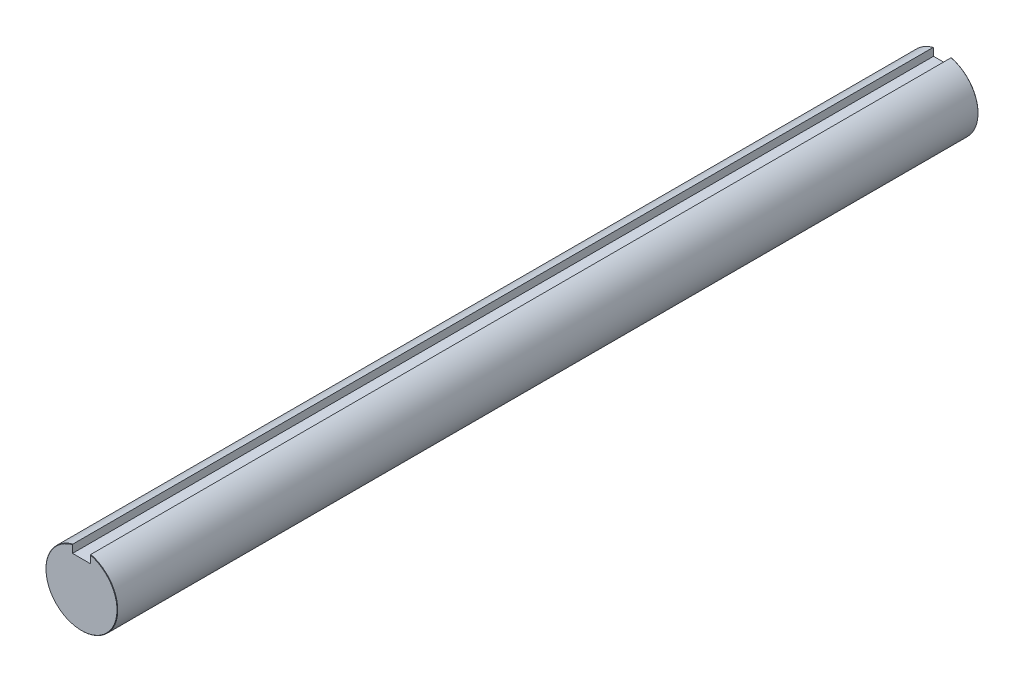
SolidWorks part; units mm, degrees
ref_plane "Front Plane" through (0, 0, 0) normal (0, 0, 1) x (1, 0, 0)
ref_plane "Top Plane" through (0, 0, 0) normal (0, 1, 0) x (1, 0, 0)
ref_plane "Right Plane" through (0, 0, 0) normal (1, 0, 0) x (0, 0, -1)
sketch "Sketch1" plane through (0, 0, 0) normal (1, 0, 0) x (0, 0, -1)
  line L0 (0, 0) -> (0, 6.35) construction
  line L1 (-76.2, 6.35) -> (76.2, 6.35)
  line L2 (-76.2, 6.35) -> (-76.2, -6.35)
  line L3 (-76.2, -6.35) -> (76.2, -6.35)
  line L4 (76.2, 6.35) -> (76.2, -6.35)
  line L5 (-76.2, 6.35) -> (76.2, -6.35) construction
  line L6 (-76.2, -6.35) -> (76.2, 6.35) construction
  line L7 (0, 0) -> (0, -6.35) construction
  point P0 (0, 0)
  point P8 (-61.595, 6.35)
  point P10 (61.595, 6.35)
  dimension "Diameter" = 12.7
  dimension "Length" = 152.4
  dimension "D1" = 14.605
  dimension "D2" = 14.605
  dimension "Keyway Length" = 152.4
sketch "Sketch2" plane through (0, 0, 0) normal (0, 0, 1) x (1, 0, 0)
  line L0 (0, 0) -> (0, 6.35) construction
  line L2 (1.5875, 4.7498) -> (-1.5875, 4.7498)
  line L3 (1.5875, 4.7498) -> (1.5875, 6.35)
  line L4 (1.5875, 6.35) -> (-1.5875, 6.35)
  line L5 (-1.5875, 4.7498) -> (-1.5875, 6.35)
  line L6 (1.5875, 4.7498) -> (-1.5875, 6.35) construction
  line L7 (1.5875, 6.35) -> (-1.5875, 4.7498) construction
  circle A0 centre (0, 0) radius 6.35
  point P3 (0, 5.5499)
  dimension "Keyway Width" = 3.175
  dimension "Keyway Depth" = 1.6002
sketch "Sketch3" plane through (0, 0, 0) normal (0, 0, 1) x (1, 0, 0)
  line L1 (-1.5875, 4.7498) -> (-1.5875, 6.35) construction
  line L2 (1.5875, 4.7498) -> (-1.5875, 4.7498) construction
  line L3 (1.5875, 4.7498) -> (1.5875, 6.35) construction
  line L5 (-1.5875, 4.7498) -> (-1.5875, 6.1484)
  line L6 (1.5875, 4.7498) -> (-1.5875, 4.7498)
  line L7 (1.5875, 4.7498) -> (1.5875, 6.1484)
  arc A1 (-1.5875, 6.1484) -> (1.5875, 6.1484) centre (0, 0) ccw
  circle A2 centre (0, 0) radius 6.35 construction
extrude "Boss-Extrude1" add sketch "Sketch3" along normal up to vertex (76.2 mm away) and the other way up to vertex (76.2 mm away) up to point (0, 6.35, 76.2) other way up to point (0, 6.35, -76.2)
chamfer "Chamfer1" distance 0.0635 angle 45 2 edges at (0, -6.35, 76.2) (0, -6.35, -76.2)
equation "\"D2@Sketch1\"=1.15*\"Diameter@Sketch1\""
equation "\"D1@Sketch1\"=\"D2@Sketch1\""
equation "\"D1@Chamfer1\"=\"Diameter@Sketch1\"*.005"
